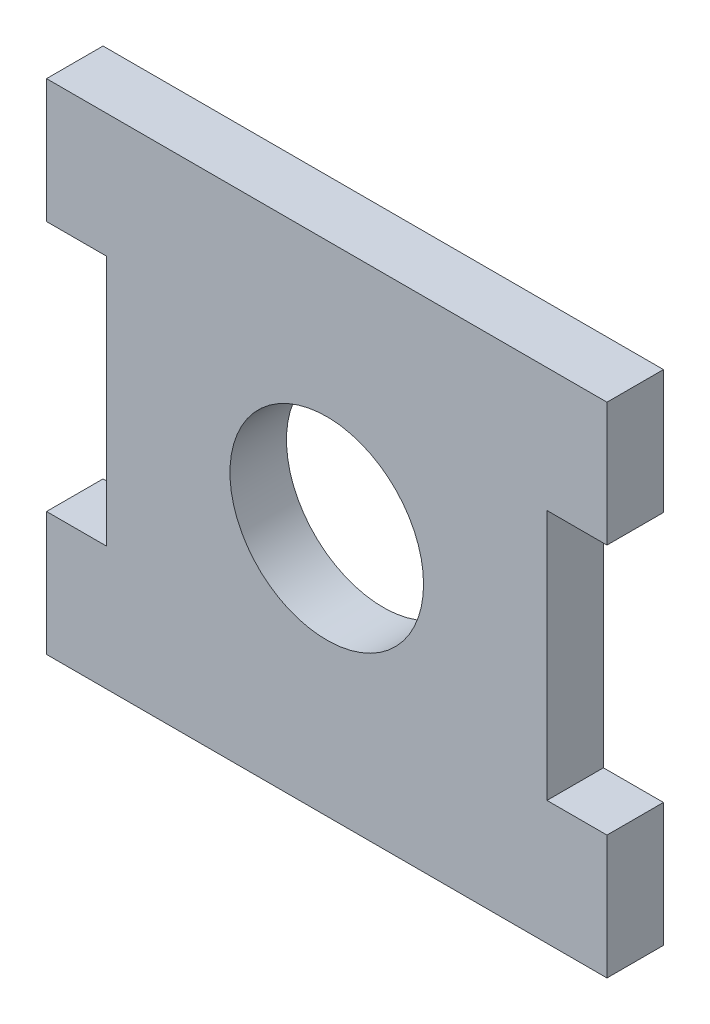
SolidWorks part; units mm, degrees
material "Oak"
ref_plane "Front Plane" through (0, 0, 0) normal (0, 0, 1) x (1, 0, 0)
ref_plane "Top Plane" through (0, 0, 0) normal (0, 1, 0) x (1, 0, 0)
ref_plane "Right Plane" through (0, 0, 0) normal (1, 0, 0) x (0, 0, -1)
sketch "Sketch1" plane through (0, 0, 0) normal (0, 0, 1) x (1, 0, 0)
  line L0 (0, 0) -> (56.6928, 0)
  line L1 (56.6928, 0) -> (56.6928, 12.5222)
  line L2 (56.6928, 12.5222) -> (50.6222, 12.5222)
  line L3 (50.6222, 12.5222) -> (50.6222, 37.9222)
  line L4 (50.6222, 37.9222) -> (56.6928, 37.9222)
  line L5 (56.6928, 37.9222) -> (56.6928, 50.4444)
  line L6 (56.6928, 50.4444) -> (0, 50.4444)
  line L7 (0, 50.4444) -> (0, 37.9222)
  line L8 (0, 37.9222) -> (6.0706, 37.9222)
  line L9 (6.0706, 37.9222) -> (6.0706, 12.5222)
  line L10 (6.0706, 12.5222) -> (0, 12.5222)
  line L11 (0, 12.5222) -> (0, 0)
  circle A0 centre (28.3464, 25.2222) radius 9.7917
  point P15 (28.3464, 50.4444)
  point P16 (28.3464, 0)
  point P17 (50.6222, 25.2222)
  point P18 (0, 0)
  point P19 (6.0706, 25.2222)
  point P20 (0, 0)
  point P21 (0, 0)
  point P22 (-148.5679, 35.2735)
  dimension "D5" = 19.5834
  dimension "D1" = 56.6928
  dimension "D2" = 50.4444
  dimension "D3" = 25.4
  dimension "D4" = 6.0706
extrude "Boss-Extrude1" add sketch "Sketch1" along normal blind 5.715
